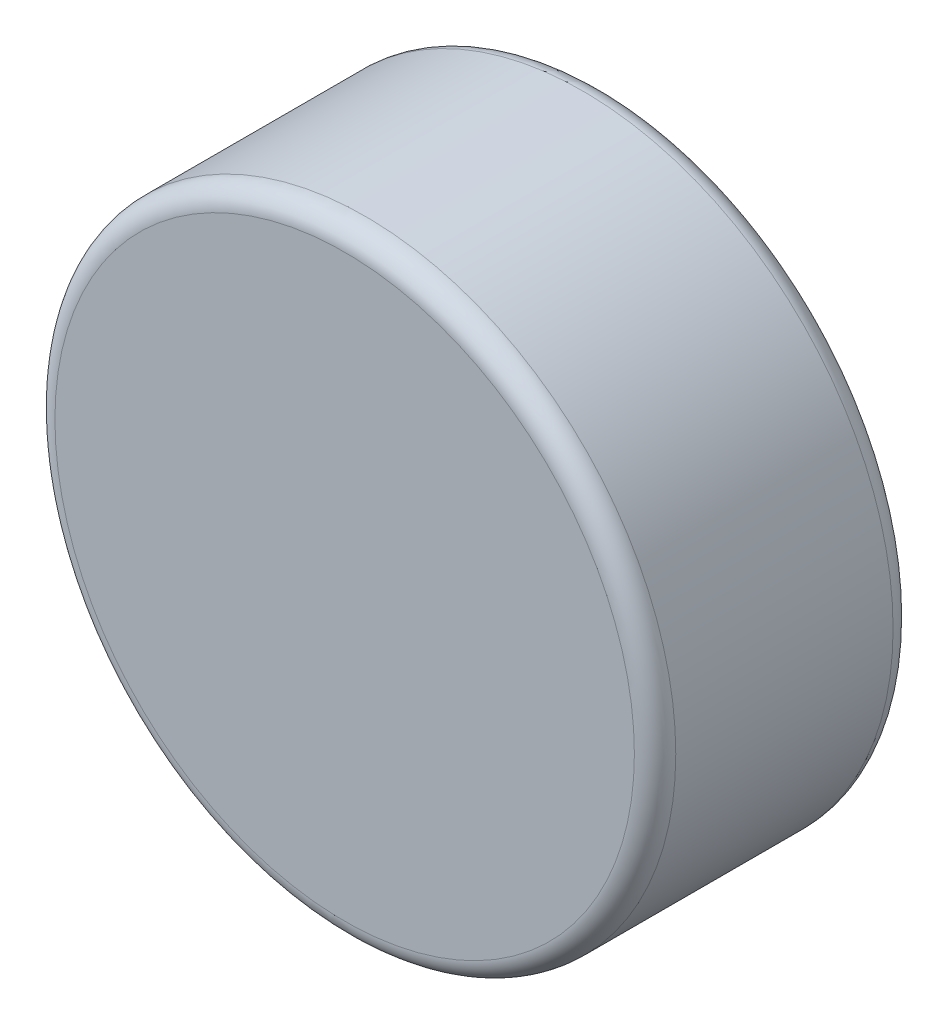
SolidWorks part; units mm, degrees
ref_plane "前视基准面" through (0, 0, 0) normal (0, 0, 1) x (1, 0, 0)
ref_plane "上视基准面" through (0, 0, 0) normal (0, 1, 0) x (1, 0, 0)
ref_plane "右视基准面" through (0, 0, 0) normal (1, 0, 0) x (0, 0, -1)
other "Configuration Table"
sketch "草图1" plane through (0, 0, 0) normal (0, 0, 1) x (1, 0, 0)
  circle A0 centre (0, 0) radius 3
  dimension "D1" = 6
extrude "凸台-拉伸1" add sketch "草图1" along normal blind 2.5
fillet "圆角1" radius 0.2 2 edges at (3, 0, 0) (3, 0, 2.5)
